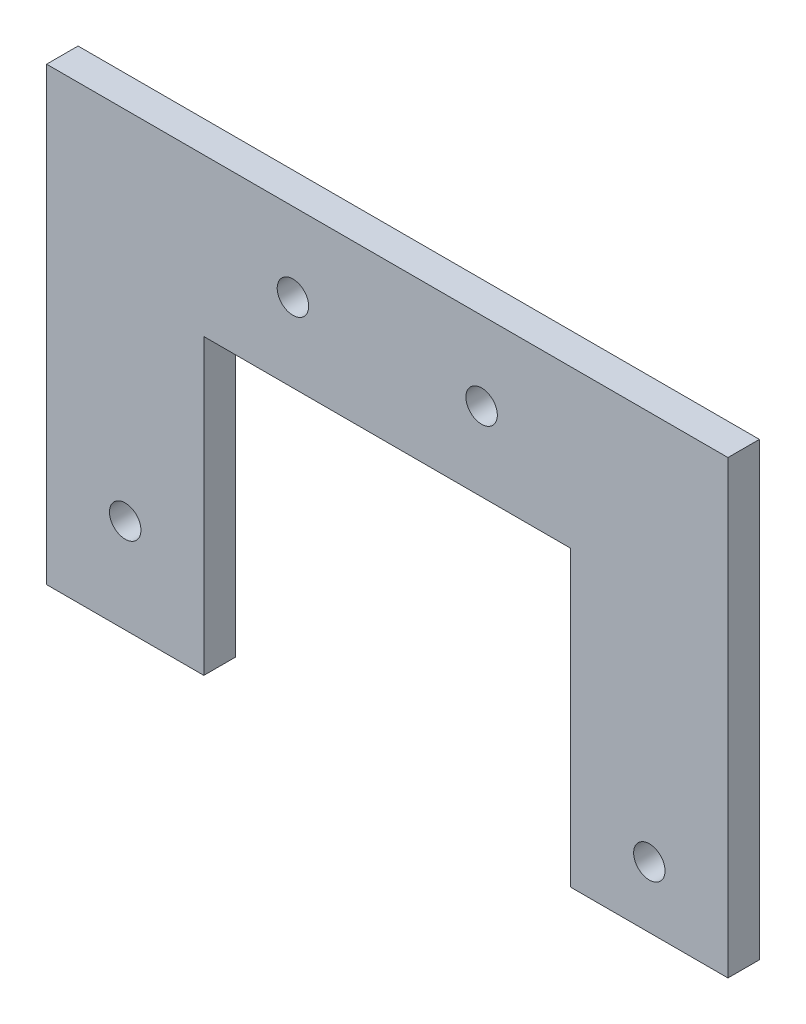
SolidWorks part; units mm, degrees
ref_plane "前视基准面" through (0, 0, 0) normal (0, 0, 1) x (1, 0, 0)
ref_plane "上视基准面" through (0, 0, 0) normal (0, 1, 0) x (1, 0, 0)
ref_plane "右视基准面" through (0, 0, 0) normal (1, 0, 0) x (0, 0, -1)
sketch "草图1" plane through (0, 0, 0) normal (0, 0, 1) x (1, 0, 0)
  line L0 (0, 0) -> (65, 0)
  line L1 (65, 0) -> (65, -43)
  line L2 (65, -43) -> (50, -43)
  line L3 (50, -43) -> (50, -15)
  line L4 (50, -15) -> (15, -15)
  line L5 (15, -15) -> (15, -43)
  line L6 (15, -43) -> (0, -43)
  line L7 (0, -43) -> (0, 0)
  dimension "D1" = 43
  dimension "D2" = 65
  dimension "D3" = 15
  dimension "D4" = 15
  dimension "D5" = 15
extrude "凸台-拉伸1" add sketch "草图1" along normal blind 3
sketch "草图2" plane through (0, 0, 3) normal (0, 0, 1) x (1, 0, 0)
  line L0 (0, -43) -> (15, -43) construction
  line L1 (65, 0) -> (0, 0) construction
  line L2 (50, -43) -> (65, -43) construction
  circle A0 centre (57.5, -37.158) radius 1.5
  circle A1 centre (7.5, -34) radius 1.5
  circle A2 centre (23.5, -7.5) radius 1.5
  circle A3 centre (41.5, -7.5) radius 1.5
  point P12 (7.5, -43)
  point P15 (57.5, -43)
  point P16 (0, 0)
  dimension "D1" = 3
  dimension "D2" = 9
  dimension "D3" = 16
  dimension "D4" = 16
  dimension "D5" = 7.5
extrude "切除-拉伸1" cut sketch "草图2" against normal blind 3
